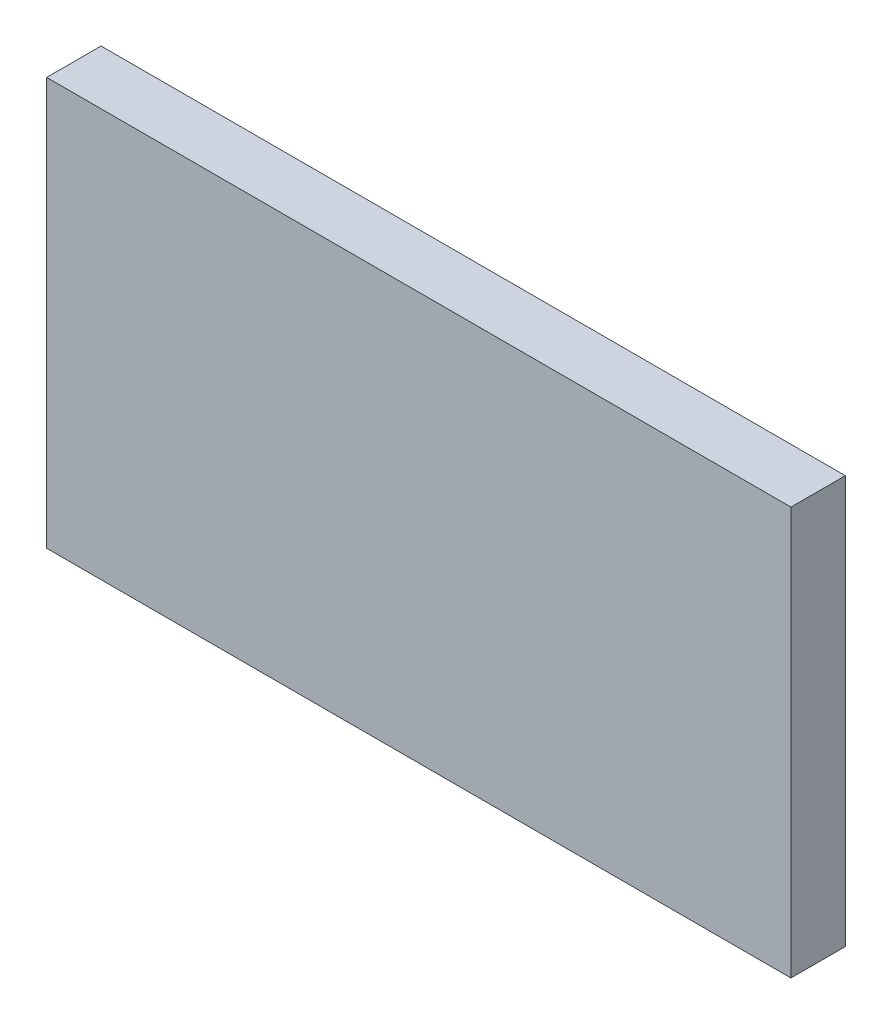
SolidWorks part; units mm, degrees
ref_plane "Front Plane" through (0, 0, 0) normal (0, 0, 1) x (1, 0, 0)
ref_plane "Top Plane" through (0, 0, 0) normal (0, 1, 0) x (1, 0, 0)
ref_plane "Right Plane" through (0, 0, 0) normal (1, 0, 0) x (0, 0, -1)
sketch "CurveSketch" plane through (0, 0, 0) normal (0, 0, 1) x (1, 0, 0)
  line L0 (-20.0525, -1.8635) -> (11.6665, -1.8635)
  line L1 (11.6665, -1.8635) -> (11.6665, 15.5175)
  line L2 (11.6665, 15.5175) -> (-20.0525, 15.5175)
  line L3 (-20.0525, 15.5175) -> (-20.0525, -1.8635)
extrude "CurveBoss" add sketch "CurveSketch" along normal mid plane 2.317
